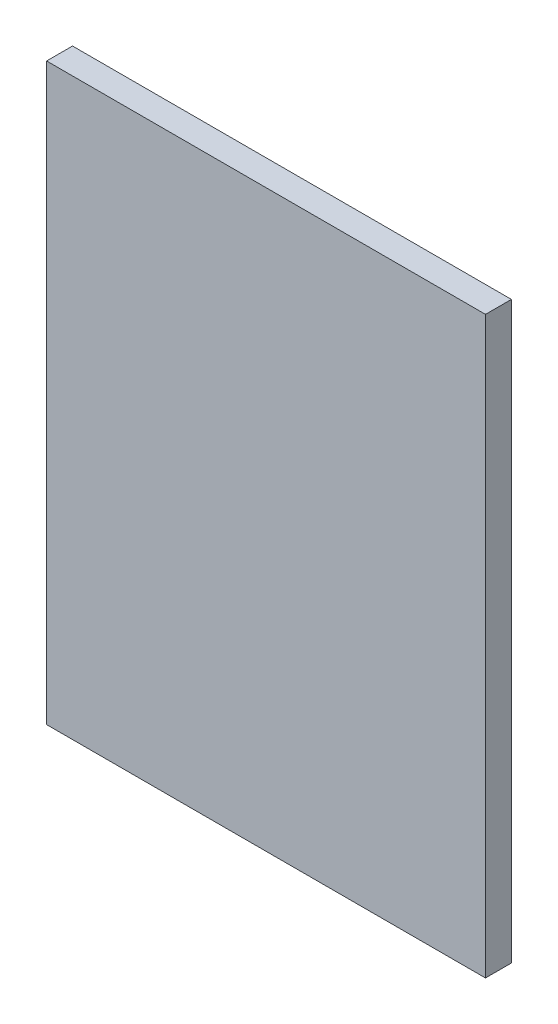
SolidWorks part; units mm, degrees
ref_plane "Plano frontal" through (0, 0, 0) normal (0, 0, 1) x (1, 0, 0)
ref_plane "Plano superior" through (0, 0, 0) normal (0, 1, 0) x (1, 0, 0)
ref_plane "Plano direito" through (0, 0, 0) normal (1, 0, 0) x (0, 0, -1)
sketch "Esboço1" plane through (0, 0, 0) normal (0, 0, 1) x (1, 0, 0)
  line L1 (0, 0) -> (420, 0)
  line L2 (0, 0) -> (0, 550)
  line L3 (0, 550) -> (420, 550)
  line L4 (420, 0) -> (420, 550)
  dimension "D1" = 420
  dimension "D2" = 550
extrude "Ressalto-extrusão1" add sketch "Esboço1" along normal blind 24.8
